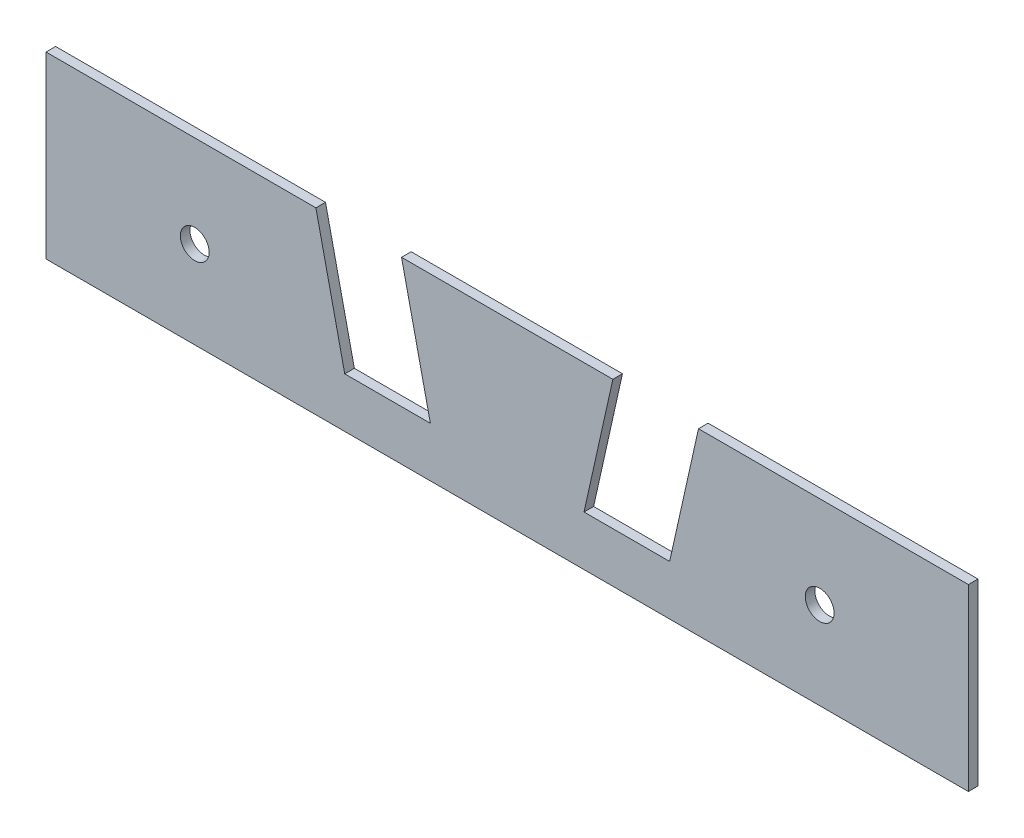
SolidWorks part; units mm, degrees
ref_plane "Спереди" through (0, 0, 0) normal (0, 0, 1) x (1, 0, 0)
ref_plane "Сверху" through (0, 0, 0) normal (0, 1, 0) x (1, 0, 0)
ref_plane "Справа" through (0, 0, 0) normal (1, 0, 0) x (0, 0, -1)
sketch "Эскиз1" plane through (0, 0, 0) normal (0, 0, 1) x (1, 0, 0)
  line L0 (-19.9097, -34.7962) -> (-16.9078, -48.261)
  line L5 (-48, -34.7962) -> (-19.9097, -34.7962)
  line L6 (-48, -34.7962) -> (-48, -53.4542)
  line L7 (-48, -53.4542) -> (48, -53.4542)
  line L8 (48, -34.7962) -> (48, -53.4542)
  line L9 (-16.9078, -48.261) -> (-7.9953, -48.261)
  line L10 (-7.9953, -48.261) -> (-10.9972, -34.7962)
  line L11 (-10.9972, -34.7962) -> (10.9972, -34.7962)
  line L12 (10.9972, -34.7962) -> (7.9953, -48.261)
  line L13 (7.9953, -48.261) -> (16.9078, -48.261)
  line L14 (16.9078, -48.261) -> (19.9097, -34.7962)
  line L15 (19.9097, -34.7962) -> (48, -34.7962)
  line L16 (-10.9972, -34.7962) -> (10.9972, -34.7962)
  circle A0 centre (32.5214, -44.3645) radius 1.5
  circle A1 centre (-32.5214, -44.3645) radius 1.5
extrude "Бобышка-Вытянуть1" add sketch "Эскиз1" along normal blind 1 contours L15 L14 L13 L12 L11 L10 L9 L0 L5 L6 L7 L8 A1 A0
